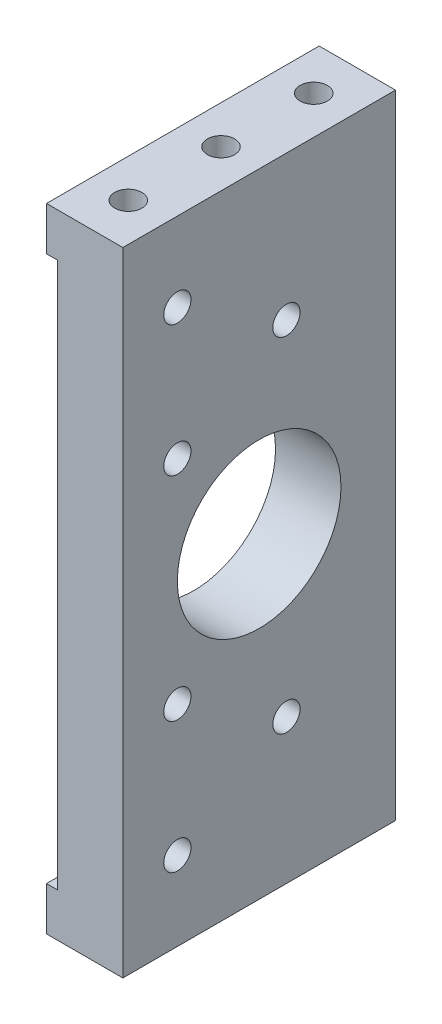
SolidWorks part; units mm, degrees
material "6061 合金"
ref_plane "前视基准面" through (0, 0, 0) normal (0, 0, 1) x (1, 0, 0)
ref_plane "上视基准面" through (0, 0, 0) normal (0, 1, 0) x (1, 0, 0)
ref_plane "右视基准面" through (0, 0, 0) normal (1, 0, 0) x (0, 0, -1)
sketch "草图1" plane through (0, 0, 0) normal (0, 0, 1) x (1, 0, 0)
  line L0 (0, 21.2234) -> (0, -15.6915) construction
  line L1 (-35.1073, 0) -> (42.2892, 0) construction
  line L2 (-81, -29) -> (86, -29)
  line L3 (-86, -29) -> (-86, -34)
  line L4 (-86, -34) -> (86, -34)
  line L5 (86, -29) -> (86, -34)
  line L8 (-86, -29) -> (-86, 29)
  line L9 (-86, 29) -> (-81, 29)
  line L10 (-81, -29) -> (-81, 29)
  dimension "D1" = 5
  dimension "D2" = 172
  dimension "D3" = 63
  dimension "D4" = 5
  dimension "D5" = 34
extrude "凸台-拉伸1" add sketch "草图1" along normal blind 25
sketch "草图2" plane through (0, 0, 25) normal (0, 0, 1) x (1, 0, 0)
  line L0 (0, 0) -> (-100.8625, 0) construction
  line L1 (-86, 29) -> (-86, -34) construction
  line L2 (-86, 25) -> (-85, 25)
  line L3 (-86, 25) -> (-86, -25)
  line L4 (-86, -25) -> (-85, -25)
  line L5 (-85, 25) -> (-85, -25)
  dimension "D1" = 1
  dimension "D2" = 50
extrude "切除-拉伸1" cut sketch "草图2" against normal through all
sketch "草图3" plane through (0, 0, 25) normal (0, 0, 1) x (1, 0, 0)
  line L0 (0, -34) -> (0, 0) construction
  line L1 (-86, -34) -> (86, -34) construction
  line L2 (86, -29) -> (-81, -29) construction
  line L3 (-26, -29) -> (26, -29)
  line L4 (-26, -29) -> (-26, -28)
  line L5 (-26, -28) -> (26, -28)
  line L6 (26, -29) -> (26, -28)
  dimension "D1" = 52
  dimension "D2" = 1
extrude "凸台-拉伸2" add sketch "草图3" against normal up to surface (25 mm away) up to face at (-50.4, -6.8, 0)
sketch "草图4" plane through (0, 0, 25) normal (0, 0, 1) x (1, 0, 0)
  line L1 (-81, -29) -> (-79, -29)
  line L2 (-81, -29) -> (-81, -28)
  line L3 (-81, -28) -> (-79, -28)
  line L4 (-79, -29) -> (-79, -28)
  dimension "D1" = 2
  dimension "D2" = 1
extrude "凸台-拉伸3" add sketch "草图4" against normal up to surface (25 mm away) up to face at (-36, -13, 0)
sketch "草图5" plane through (0, 0, 25) normal (0, 0, 1) x (1, 0, 0)
  line L0 (86, -29) -> (26, -29) construction
  line L1 (79, -29) -> (77, -29)
  line L2 (79, -29) -> (79, -28)
  line L3 (79, -28) -> (77, -28)
  line L4 (77, -29) -> (77, -28)
  line L5 (86, -34) -> (86, -29) construction
  dimension "D1" = 1
  dimension "D2" = 2
  dimension "D3" = 7
extrude "凸台-拉伸4" add sketch "草图5" against normal up to surface (25 mm away) up to face at (-41.375, -14.875, 0)
sketch "草图6" plane through (0, 0, 25) normal (0, 0, 1) x (1, 0, 0)
  line L0 (0, 0) -> (0, -34) construction
  line L1 (-86, -34) -> (86, -34) construction
  line L3 (-26, -34) -> (-15, -34)
  line L4 (-26, -34) -> (-26, -33)
  line L5 (-26, -33) -> (-15, -33)
  line L6 (-15, -34) -> (-15, -33)
  dimension "D1" = 11
  dimension "D2" = 1
  dimension "D3" = 15
extrude "切除-拉伸2" cut sketch "草图6" against normal through all
mirror "镜向1" about plane through (0, 0, 0) normal (1, 0, 0) of "切除-拉伸2"
sketch "草图7" plane through (0, -34, 0) normal (0, -1, 0) x (1, 0, 0)
  line L0 (-15, 12.5) -> (15, 12.5) construction
  line L1 (-15, 0) -> (-15, 25) construction
  line L2 (15, 0) -> (15, 25) construction
  line L3 (0, 25) -> (0, 0) construction
  line L4 (-15, 25) -> (15, 25) construction
  circle A0 centre (0, 12.5) radius 8.5
  dimension "D1" = 17
extrude "切除-拉伸3" cut sketch "草图7" against normal through all
sketch "草图8" plane through (0, -28, 0) normal (0, 1, 0) x (1, 0, 0)
  circle A0 centre (0, -12.5) radius 9.5
  dimension "D1" = 19
extrude "切除-拉伸4" cut sketch "草图8" against normal blind 5
sketch "草图9" plane through (0, 0, 0) normal (0, 0, -1) x (-1, 0, 0)
  line L1 (81, 29) -> (79, 29)
  line L2 (81, 29) -> (81, 24)
  line L3 (81, 24) -> (79, 24)
  line L4 (79, 29) -> (79, 24)
  dimension "D1" = 5
  dimension "D2" = 2
extrude "凸台-拉伸5" add sketch "草图9" against normal up to surface (25 mm away) up to face at (-12.5, -22.1429, 25)
sketch "草图11" plane through (0, -34, 0) normal (0, -1, 0) x (1, 0, 0)
  line L0 (82.5, 25) -> (82.5, 0) construction
  line L1 (26, 25) -> (86, 25) construction
  line L2 (26, 0) -> (86, 0) construction
  line L3 (86, 25) -> (86, 0) construction
  line L4 (86, 12.5) -> (82.5, 12.5) construction
  point P10 (82.5, 21)
  point P11 (82.5, 4)
  point P13 (82.5, 12.5)
  dimension "D2" = 4
  dimension "D1" = 3.5
hole_wizard "孔1" positions "3D草图1" profile "草图12" legacy end condition up to next
sketch3d "3D草图1"
  point P0 (82.5, -34, 21)
  point P3 (82.5, -34, 12.5)
  point P6 (82.5, -34, 4)
sketch "草图12" plane through (82.5, -34, 21) normal (1, 0, 0) x (0, 0, -1)
  line L0 (0, 0) -> (0, 5)
  line L1 (0, 5) -> (1.7, 5)
  line L2 (1.7, 5) -> (1.7, 3)
  line L3 (1.7, 3) -> (3, 3)
  line L4 (3, 3) -> (3, 0)
  line L5 (3, 0) -> (0, 0)
  line L6 (0, 110) -> (0, -10) construction
  dimension "直径" = 3.4
  dimension "深度" = 5
  dimension "柱坑直径" = 6
  dimension "柱坑深度" = 3
sketch "草图13" plane through (0, 29, 0) normal (0, 1, 0) x (1, 0, 0)
  line L0 (-82.5, 0) -> (-82.5, -25) construction
  line L1 (-79, 0) -> (-86, 0) construction
  line L2 (-79, -25) -> (-86, -25) construction
  line L3 (-86, -12.5) -> (-79, -12.5) construction
  line L4 (-86, -25) -> (-86, 0) construction
  line L5 (-79, -25) -> (-79, 0) construction
  circle A0 centre (-82.5, -12.5) radius 1.5
  circle A1 centre (-82.5, -4) radius 1.5
  circle A2 centre (-82.5, -21) radius 1.5
  dimension "D1" = 3
  dimension "D2" = 4
sketch "草图14" plane through (0, -33, 0) normal (0, -1, 0) x (1, 0, 0)
  line L0 (0, 0) -> (0, 48.2604) construction
  line L1 (-26, 12.5) -> (26, 12.5) construction
  line L2 (-26, 0) -> (-26, 25) construction
  line L3 (26, 0) -> (26, 25) construction
  line L4 (-26, 0) -> (-26, 25) construction
  line L7 (20.5, 25) -> (20.5, 0) construction
  line L8 (15, 25) -> (26, 25) construction
  line L9 (15, 0) -> (26, 0) construction
  circle A0 centre (-23, 20) radius 1.5
  circle A1 centre (-23, 5) radius 1.5
  dimension "D1" = 3
  dimension "D2" = 15
  dimension "D3" = 3
extrude "切除-拉伸8" cut sketch "草图14" against normal up to next
cosmetic thread "装饰螺纹线4" parameters "D2"=3.2
cosmetic thread "装饰螺纹线5" parameters "D2"=3.2
mirror "镜向2" about plane through (0, 0, 0) normal (1, 0, 0) of "切除-拉伸8"
cosmetic thread "装饰螺纹线6" parameters "D2"=3.2
cosmetic thread "装饰螺纹线7" parameters "D2"=3.2
sketch "草图22" plane through (-81, 0, 0) normal (1, 0, 0) x (0, 0, -1)
  line L4 (0, -28) -> (0, 24)
  line L5 (0, 24) -> (-25, 24)
  line L6 (-25, 24) -> (-25, -28)
  line L7 (-25, -28) -> (0, -28)
  line L8 (0, -28) -> (0, 24)
  line L9 (0, 24) -> (-25, 24)
  line L10 (-25, 24) -> (-25, -28)
  line L11 (-25, -28) -> (0, -28)
  dimension "D1" = 0
extrude "凸台-拉伸9" add sketch "草图22" along normal up to surface (2 mm away) up to face at (-79, 26.5, 12.5)
sketch "草图15" plane through (-85, 0, 0) normal (-1, 0, 0) x (0, 0, 1)
  circle A0 centre (20, 21.75) radius 1.25
  circle A1 centre (20, 9.75) radius 1.25
  circle A2 centre (10, 15.75) radius 1.25
  circle A3 centre (20, -9.75) radius 1.25
  circle A4 centre (20, -21.75) radius 1.25
  circle A5 centre (10, -15.75) radius 1.25
  dimension "D1" = 2.5
sketch "草图16" plane through (0, -34, 0) normal (0, -1, 0) x (1, 0, 0)
  line L1 (-73, 20) -> (-30, 20)
  line L2 (-78, 15) -> (-78, 10)
  line L3 (-73, 5) -> (-30, 5)
  line L4 (-25, 15) -> (-25, 10)
  line L5 (-86, 25) -> (-86, 0) construction
  line L6 (-15, 0) -> (-15, 25) construction
  line L7 (-86, 25) -> (-26, 25) construction
  line L8 (-86, 0) -> (-26, 0) construction
  arc A0 (-30, 5) -> (-25, 10) centre (-30, 10) ccw
  arc A1 (-30, 20) -> (-25, 15) centre (-30, 15) cw
  arc A2 (-78, 10) -> (-73, 5) centre (-73, 10) ccw
  arc A3 (-73, 20) -> (-78, 15) centre (-73, 15) ccw
  dimension "D5" = 5
  dimension "D1" = 8
  dimension "D2" = 10
  dimension "D3" = 5
  dimension "D4" = 5
extrude "切除-拉伸10" cut sketch "草图16" against normal up to next
mirror "镜向3" about plane through (0, 0, 0) normal (1, 0, 0) of "切除-拉伸10"
sketch "草图17" plane through (-85, 0, 0) normal (-1, 0, 0) x (0, 0, 1)
  line L0 (0, -25) -> (0, 25) construction
  circle A0 centre (12.5, 0) radius 7.5
  dimension "D1" = 12.5
  dimension "D2" = 15
extrude "切除-拉伸11" cut sketch "草图17" against normal up to next
sketch "草图18" plane through (0, 0, 25) normal (0, 0, 1) x (1, 0, 0)
  line L0 (-79, -29) -> (-86, -29)
  line L1 (-86, -25) -> (-86, -34) construction
  line L2 (-86, -29) -> (-86, -34)
  line L3 (-86, -34) -> (86, -34)
  line L4 (86, -34) -> (86, -25.7591)
  line L5 (86, -25.7591) -> (-79, -25.7591)
  line L6 (-79, -25.7591) -> (-79, -29)
extrude "切除-拉伸12" cut sketch "草图18" against normal blind 60
hole_wizard "M3 螺纹孔1" positions "3D草图2" profile "草图23" tap size "M3" standard "GB"
sketch3d "3D草图2"
  point P0 (-85, 21.75, 20)
  point P3 (-85, 9.75, 20)
  point P6 (-85, 15.75, 10)
  point P9 (-85, -9.75, 20)
  point P12 (-85, -21.75, 20)
  point P15 (-85, -15.75, 10)
sketch "草图23" plane through (-85, 21.75, 20) normal (0, 1, 0) x (0, 0, 1)
  line L0 (0, 0) -> (0, 9.2511)
  line L1 (0, 9.2511) -> (1.25, 8.5)
  line L2 (1.25, 8.5) -> (1.25, 0)
  line L5 (1.25, 0) -> (0, 0)
  line L10 (0, 9.2511) -> (-1.25, 8.5) construction
  line L11 (0, -6.35) -> (0, 107.95) construction
  dimension "螺纹孔钻头直径" = 2.5
  dimension "螺纹孔钻头深度" = 8.5
  dimension "导头角度" = 118
cosmetic thread "孔螺蚊线1" parameters "D1"=6, "D2"=3
cosmetic thread "孔螺蚊线2" parameters "D1"=6, "D2"=3
cosmetic thread "孔螺蚊线3" parameters "D1"=6, "D2"=3
cosmetic thread "孔螺蚊线4" parameters "D1"=6, "D2"=3
cosmetic thread "孔螺蚊线5" parameters "D1"=6, "D2"=3
cosmetic thread "孔螺蚊线6" parameters "D1"=6, "D2"=3
hole_wizard "M3 螺纹孔2" positions "3D草图3" profile "草图24" tap size "M3" standard "GB"
sketch3d "3D草图3"
  point P0 (-82.5, 29, 21)
  point P3 (-82.5, 29, 12.5)
  point P6 (-82.5, 29, 4)
sketch "草图24" plane through (-82.5, 29, 21) normal (1, 0, 0) x (0, 0, 1)
  line L0 (0, 0) -> (0, 5.7511)
  line L1 (0, 5.7511) -> (1.25, 5)
  line L2 (1.25, 5) -> (1.25, 0)
  line L5 (1.25, 0) -> (0, 0)
  line L10 (0, 5.7511) -> (-1.25, 5) construction
  line L11 (0, -6.35) -> (0, 107.95) construction
  dimension "螺纹孔钻头直径" = 2.5
  dimension "螺纹孔钻头深度" = 5
  dimension "导头角度" = 118
cosmetic thread "孔螺蚊线7" parameters "D1"=5, "D2"=3
cosmetic thread "孔螺蚊线8" parameters "D1"=5, "D2"=3
cosmetic thread "孔螺蚊线9" parameters "D1"=5, "D2"=3
ref_plane "基准面1" through (0, 0, 0) normal (0, 1, 0) x (1, 0, 0)
mirror "镜向4" about plane through (0, 0, 0) normal (0, 1, 0) of "M3 螺纹孔2"
